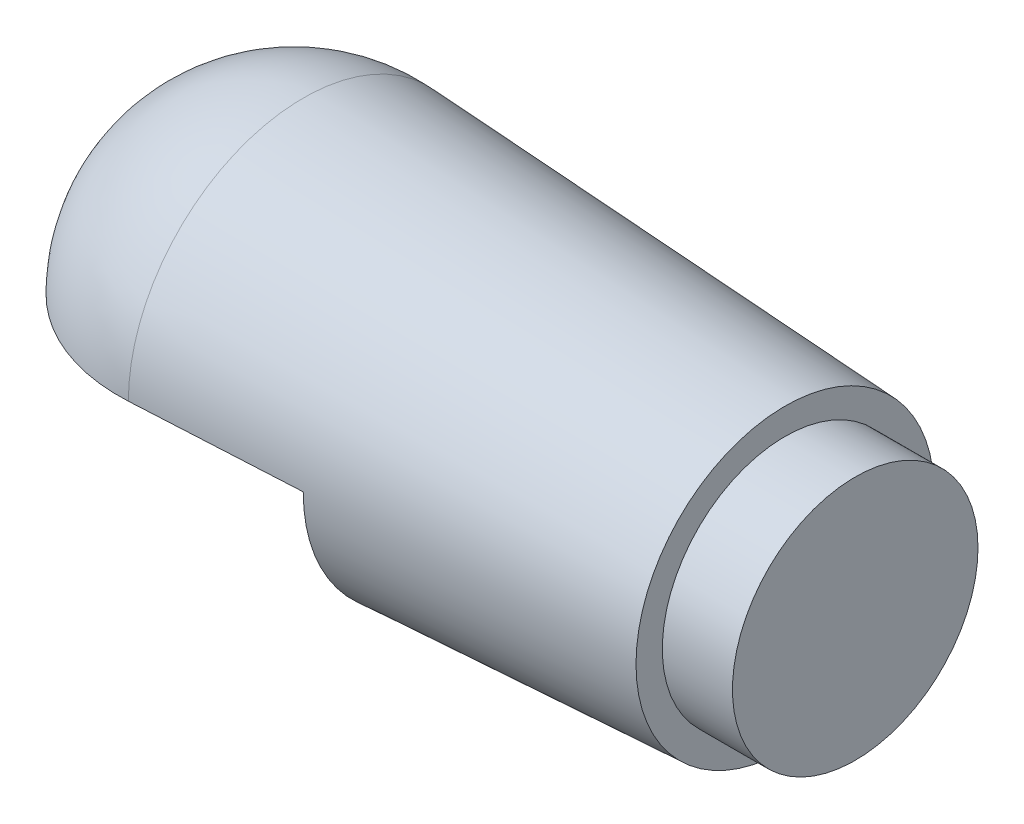
SolidWorks part; units mm, degrees
ref_plane "Front Plane" through (0, 0, 0) normal (0, 0, 1) x (1, 0, 0)
ref_plane "Top Plane" through (0, 0, 0) normal (0, 1, 0) x (1, 0, 0)
ref_plane "Right Plane" through (0, 0, 0) normal (1, 0, 0) x (0, 0, -1)
sketch "Sketch1" plane through (0, 0, 0) normal (0, 1, 0) x (1, 0, 0)
  line L0 (0, 0) -> (0, 42.5)
  line L1 (0, 42.5) -> (-137.2993, 49.927)
  line L2 (-190, 0) -> (-175, 0)
  line L3 (-105, 0) -> (0, 0)
  arc A0 (-137.2993, 49.927) -> (-190, 0) centre (-140, 0) ccw
  arc A1 (-105, 0) -> (-175, 0) centre (-140, 0) ccw
  dimension "D1" = 100
  dimension "D4" = 70
  dimension "D2" = 140
  dimension "D3" = 42.5
revolve "Revolve1" add sketch "Sketch1" angle 360 about L3
sketch "Sketch2" plane through (0, 0, 0) normal (0, 1, 0) x (1, 0, 0)
  line L1 (-190, -50) -> (-90, -50)
  line L2 (-190, -50) -> (-190, 50)
  line L3 (-190, 50) -> (-90, 50)
  line L4 (-90, -50) -> (-90, 50)
  line L5 (-190, -50) -> (-90, 50) construction
  line L6 (-190, 50) -> (-90, -50) construction
  point P0 (-140, 0)
  dimension "D1" = 140
  dimension "D2" = 100
  dimension "D3" = 100
extrude "Cut-Extrude1" cut sketch "Sketch2" against normal blind 62
sketch "Sketch3" plane through (0, 0, 0) normal (1, 0, 0) x (0, 0, -1)
  circle A0 centre (0, 0) radius 35
  dimension "D1" = 70
extrude "Boss-Extrude1" add sketch "Sketch3" along normal blind 20
